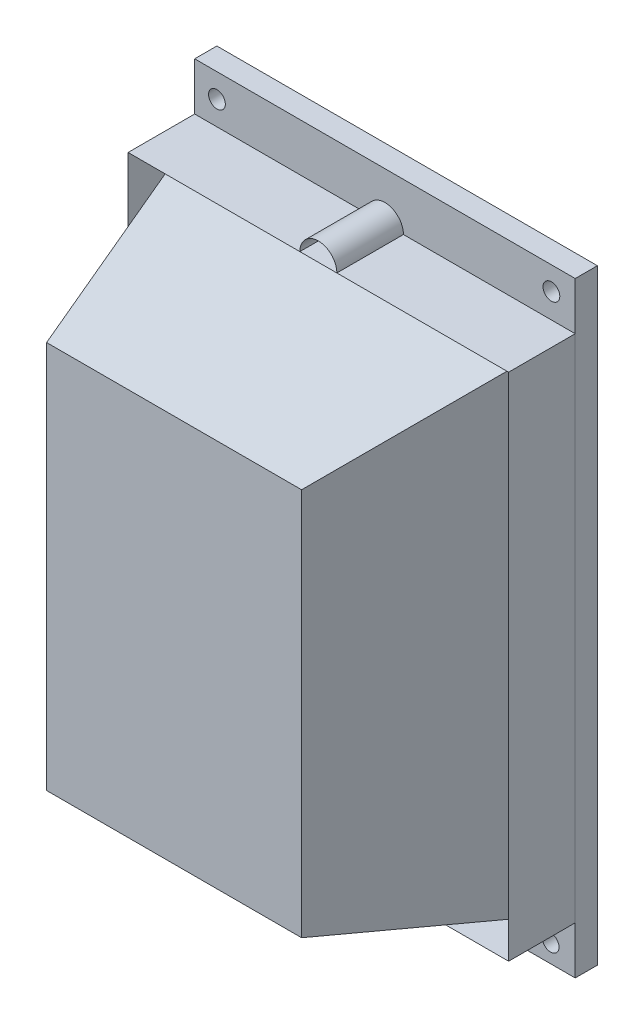
SolidWorks part; units mm, degrees
ref_plane "Front Plane" through (0, 0, 0) normal (0, 0, 1) x (1, 0, 0)
ref_plane "Top Plane" through (0, 0, 0) normal (0, 1, 0) x (1, 0, 0)
ref_plane "Right Plane" through (0, 0, 0) normal (1, 0, 0) x (0, 0, -1)
sketch "Sketch1" plane through (0, 0, 0) normal (0, 0, 1) x (1, 0, 0)
  line L1 (17.1465, -27.2945) -> (-17.1465, -27.2945)
  line L2 (17.1465, -27.2945) -> (17.1465, 27.2945)
  line L3 (17.1465, 27.2945) -> (-17.1465, 27.2945)
  line L4 (-17.1465, -27.2945) -> (-17.1465, 27.2945)
  line L5 (17.1465, -27.2945) -> (-17.1465, 27.2945) construction
  line L6 (17.1465, 27.2945) -> (-17.1465, -27.2945) construction
  point P0 (0, 0)
extrude "Boss-Extrude1" add sketch "Sketch1" along normal blind 2
sketch "Sketch2" plane through (0, 0, 2) normal (0, 0, 1) x (1, 0, 0)
  line L0 (-17.1465, 27.2945) -> (-17.1465, -27.2945) construction
  line L1 (17.1465, -22.9872) -> (-17.1465, -22.9872)
  line L2 (17.1465, -22.9872) -> (17.1465, 22.9872)
  line L3 (17.1465, 22.9872) -> (-17.1465, 22.9872)
  line L4 (-17.1465, -22.9872) -> (-17.1465, 22.9872)
  line L5 (17.1465, -22.9872) -> (-17.1465, 22.9872) construction
  line L6 (17.1465, 22.9872) -> (-17.1465, -22.9872) construction
  arc A0 (1.6669, 22.9872) -> (-1.6669, 22.9872) centre (0, 22.9872) ccw
  arc A1 (-1.665, -22.9872) -> (1.665, -22.9872) centre (0, -22.9872) ccw
  point P0 (0, 0)
  dimension "D1" = 3.3337
  dimension "D2" = 3.33
surface "Surface-Extrude1" sketch "Sketch2" parameters "D1"=6
sketch "Sketch3" plane through (0, 0, 2) normal (0, 0, 1) x (1, 0, 0)
  line L1 (16.581, -22.5724) -> (-16.581, -22.5724)
  line L2 (16.581, -22.5724) -> (16.581, 22.5724)
  line L3 (16.581, 22.5724) -> (-16.581, 22.5724)
  line L4 (-16.581, -22.5724) -> (-16.581, 22.5724)
  line L5 (16.581, -22.5724) -> (-16.581, 22.5724) construction
  line L6 (16.581, 22.5724) -> (-16.581, -22.5724) construction
  point P0 (0, 0)
extrude "Boss-Extrude3" add sketch "Sketch3" along normal blind 19 draft 15
sketch "Sketch5" plane through (0, 0, 2) normal (0, 0, 1) x (1, 0, 0)
hole_wizard "#1-64 Tapped Hole1" positions "3DSketch1" profile "Sketch6" tap size "#1-64" standard "ANSI Inch"
sketch3d "3DSketch1"
  point P0 (15.0007, 25.2095, 2)
  point P2 (-15.1396, 25.14, 2)
  point P4 (-15.4868, -25.6956, 2)
  point P6 (14.9312, -25.6262, 2)
sketch "Sketch6" plane through (15.0007, 25.2095, 2) normal (1, 0, 0) x (0, -1, 0)
  line L0 (0, 0) -> (0, 5.3512)
  line L1 (0, 5.3512) -> (0.7556, 4.8971)
  line L2 (0.7556, 4.8971) -> (0.7556, 0)
  line L5 (0.7556, 0) -> (0, 0)
  line L10 (0, 5.3512) -> (-0.7556, 4.8971) construction
  line L11 (0, -6.35) -> (0, 107.95) construction
  dimension "Tap Drill Dia." = 1.5113
  dimension "Tap Drill Depth" = 4.8971
  dimension "Drill Angle" = 118
scale "Scale2" bodies to scale 107 scale about origin uniform scaling yes scale factor 0.5
scale "Scale4" bodies to scale 104 103 105 scale about origin uniform scaling yes scale factor 0.5
scale "Scale5" bodies to scale 109 scale about origin uniform scaling yes scale factor 0.5
scale "Scale6" bodies to scale 112 114 113 scale about origin uniform scaling yes scale factor 0.5
